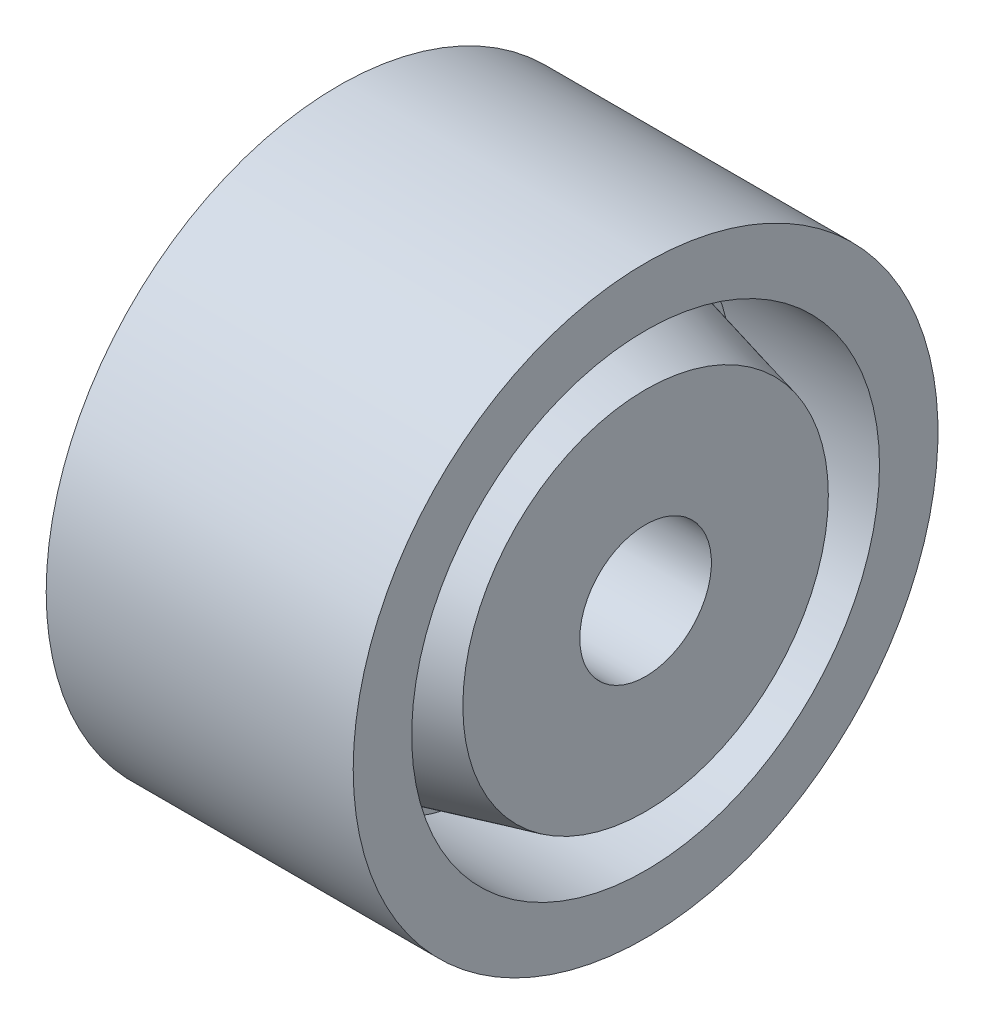
SolidWorks part; units mm, degrees
ref_plane "Front Plane" through (0, 0, 0) normal (0, 0, 1) x (1, 0, 0)
ref_plane "Top Plane" through (0, 0, 0) normal (0, 1, 0) x (1, 0, 0)
ref_plane "Right Plane" through (0, 0, 0) normal (1, 0, 0) x (0, 0, -1)
sketch "Sketch1" plane through (0, 0, 0) normal (1, 0, 0) x (0, 0, -1)
  circle A1 centre (0, 0) radius 40
extrude "Boss-Extrude1" add sketch "Sketch1" along normal blind 42 contours A1
sketch "Sketch2" plane through (0, 0, 0) normal (-1, 0, 0) x (0, 0, 1)
  circle A0 centre (0, 0) radius 9
ref_plane "Plane1" through (21, 0, 0) normal (1, 0, 0) x (0, 0, -1)
sketch "Sketch3" plane through (42, 0, 0) normal (1, 0, 0) x (0, 0, -1)
  circle A0 centre (0, 0) radius 32
extrude "Cut-Extrude2" cut sketch "Sketch3" against normal blind 20
sketch "Sketch5" plane through (42, 0, 0) normal (1, 0, 0) x (0, 0, -1)
  circle A0 centre (0, 0) radius 25
sketch "Sketch6" plane through (22, 0, 0) normal (1, 0, 0) x (0, 0, -1)
  circle A0 centre (0, 0) radius 30
loft "Loft1" add profiles "Sketch6", "Sketch5"
mirror "Mirror5" about plane through (21, 0, 0) normal (1, 0, 0) of "Cut-Extrude2", "Loft1"
extrude "Cut-Extrude4" cut sketch "Sketch2" against normal blind 13 contours A0
mirror "Mirror6" about plane through (21, 0, 0) normal (1, 0, 0) of "Cut-Extrude4"
